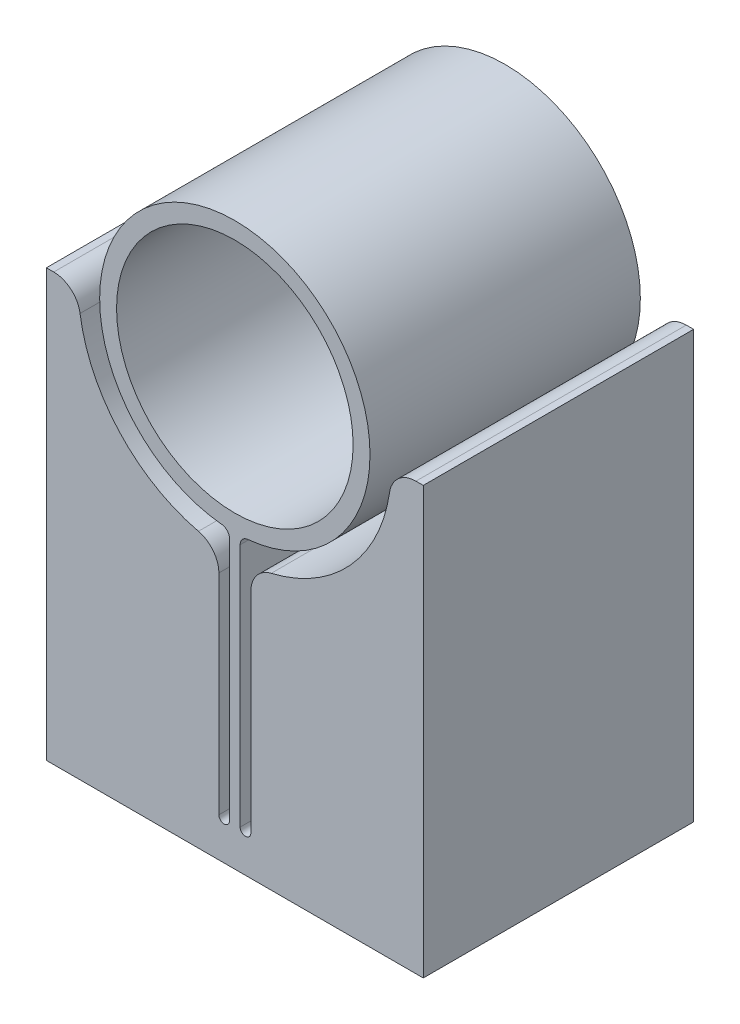
SolidWorks part; units mm, degrees
material "6061 Alloy"
ref_plane "Front Plane" through (0, 0, 0) normal (0, 0, 1) x (1, 0, 0)
ref_plane "Top Plane" through (0, 0, 0) normal (0, 1, 0) x (1, 0, 0)
ref_plane "Right Plane" through (0, 0, 0) normal (1, 0, 0) x (0, 0, -1)
sketch "Sketch1" plane through (0, 0, 0) normal (0, 0, -1) x (1, 0, 0)
  line L0 (0, 0) -> (0, 40.0837) construction
  line L1 (-17.706, 40.0837) -> (17.706, 40.0837)
  line L2 (17.706, 40.0837) -> (17.706, 30.5587)
  line L3 (17.706, 30.5587) -> (0.5, 30.5587)
  line L4 (0.5, 12.6902) -> (0.5, 30.5587)
  line L5 (-0.5, 12.6902) -> (-0.5, 30.5587)
  line L6 (-17.706, 30.5587) -> (-0.5, 30.5587)
  line L7 (-17.706, 40.0837) -> (-17.706, 30.5587)
  line L8 (0.5, 30.5587) -> (1.5, 30.5587)
  line L9 (1.5, 30.5587) -> (1.5, 14.6233)
  line L10 (17.706, 30.5587) -> (17.706, 0)
  line L11 (17.706, 0) -> (14.7, 0)
  line L12 (-17.706, 0) -> (-14.7, 0)
  line L13 (-17.706, 30.5587) -> (-17.706, 0)
  line L14 (-1.5, 30.5587) -> (-1.5, 14.6233)
  arc A0 (-0.5, 12.6902) -> (0.5, 12.6902) centre (0, 0) ccw
  circle A1 centre (0, 0) radius 11.1125
  circle A2 centre (0, 0) radius 14.7
  circle A3 centre (0, 0) radius 7.9375
  dimension "D2" = 25.4
  dimension "D3" = 22.225
  dimension "D8" = 2
  dimension "D9" = 15.875
  dimension "D1" = 40.0837
  dimension "D4" = 35.4119
  dimension "D5" = 1
  dimension "D6" = 9.525
  dimension "D7" = 1
extrude "Extrude1" add sketch "Sketch1" along normal mid plane 25.4
fillet "Bushing-side fillets" radius 0.7937 2 edges at (0.5, -12.6902, 0) (-0.5, -12.6902, 0)
fillet "Mount-side fillets" radius 0.7937 2 edges at (0.5, -30.5587, 0) (-0.5, -30.5587, 0)
hole_wizard "1/4 Mounting holes" positions "Sketch3" profile "Sketch2" tap size "1/4-20" standard "ANSI Inch"
sketch "Sketch3" plane through (0, -40.0837, 0) normal (0, -1, 0) x (1, 0, 0)
  line L0 (0, -12.7) -> (0, 12.7) construction
  line L3 (-17.706, 12.7) -> (17.706, 12.7) construction
  line L4 (-17.706, -12.7) -> (17.706, -12.7) construction
  point P0 (-12.7, 0)
  point P12 (12.7, 0)
  point P13 (0, 12.7)
  point P14 (0, 0)
  point P15 (0, 0)
  point P16 (0, 0)
  point P17 (0, 0)
  point P18 (0, 0)
  point P19 (0, 0)
  dimension "D1" = 25.4
sketch "Sketch2" plane through (-12.7, -40.0837, 0) normal (1, 0, 0) x (0, 0, -1)
  line L0 (0, 0) -> (0, 20.5838)
  line L1 (0, 20.5838) -> (2.5527, 19.05)
  line L2 (2.5527, 19.05) -> (2.5527, 0)
  line L5 (2.5527, 0) -> (0, 0)
  line L10 (0, 20.5838) -> (-2.5527, 19.05) construction
  line L11 (0, -6.35) -> (0, 107.95) construction
  dimension "Tap Drill Dia." = 5.1054
  dimension "Tap Drill Depth" = 19.05
  dimension "Drill Angle" = 118
cosmetic thread "Hole Thread1" parameters "D1"=12.7, "D2"=6.35
cosmetic thread "Hole Thread2" parameters "D1"=12.7, "D2"=6.35
sketch "Sketch6" plane through (0, 0, -12.7) normal (0, 0, -1) x (-1, 0, 0)
  line L0 (0.5, -29.6587) -> (0.5, -36.4087)
  line L1 (1.5, -36.4087) -> (1.5, -30.5587)
  line L2 (1.5, -30.5587) -> (1.4, -30.5587)
  line L3 (0, 0) -> (0, -40.0837) construction
  line L4 (-1.5, -30.5587) -> (-1.4, -30.5587)
  line L5 (-1.5, -36.4087) -> (-1.5, -30.5587)
  line L6 (-0.5, -29.6587) -> (-0.5, -36.4087)
  arc A0 (0.5, -36.4087) -> (1.5, -36.4087) centre (1, -36.4087) ccw
  arc A1 (0.5, -29.6587) -> (1.4, -30.5587) centre (1.4, -29.6587) ccw
  circle A2 centre (1, -36.4087) radius 0.5 construction
  circle A3 centre (-1, -36.4087) radius 0.5 construction
  arc A4 (-0.5, -29.6587) -> (-1.4, -30.5587) centre (-1.4, -29.6587) cw
  arc A5 (-0.5, -36.4087) -> (-1.5, -36.4087) centre (-1, -36.4087) cw
  point P8 (1, -36.9087)
  point P18 (-1, -36.9087)
  point P20 (0, 0)
  dimension "D1" = 1
  dimension "D2" = 0.9
extrude "Cut-Extrude1" cut sketch "Sketch6" against normal through all
fillet "Fillet1" radius 2.5 4 edges at (-1.5, -14.6233, 0) (1.5, -14.6233, 0) (-14.7, 0, 0) (14.7, 0, 0)
